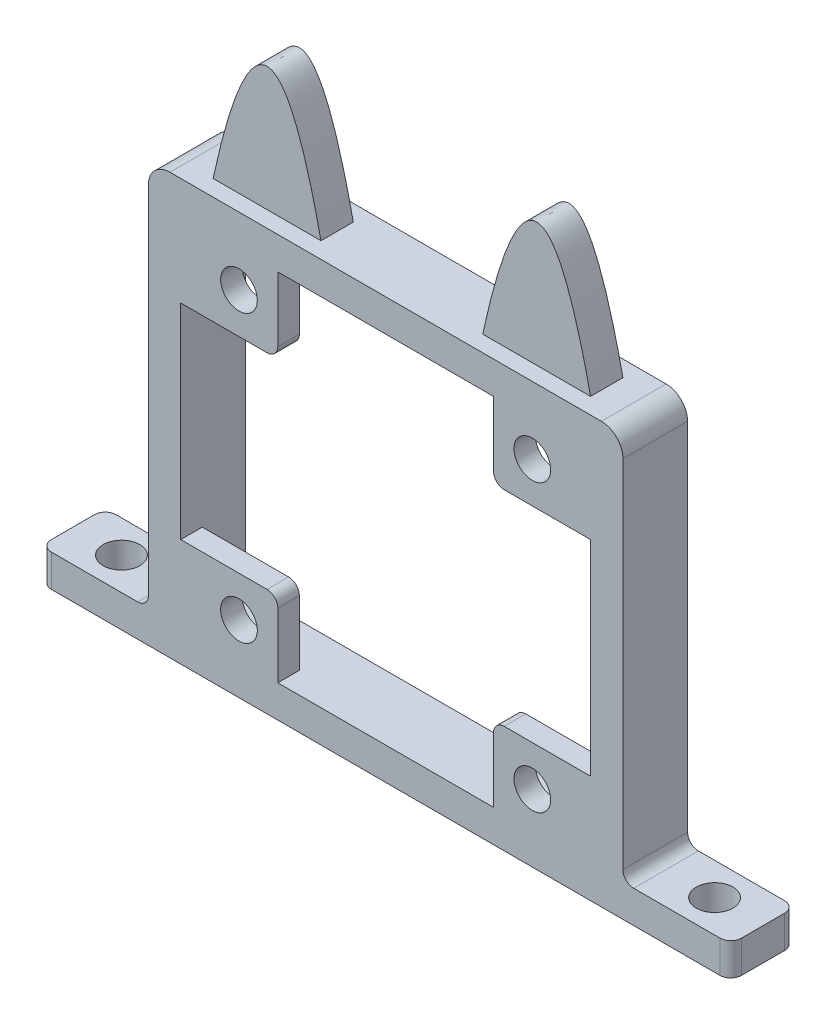
SolidWorks part; units mm, degrees
ref_plane "前视基准面" through (0, 0, 0) normal (0, 0, 1) x (1, 0, 0)
ref_plane "上视基准面" through (0, 0, 0) normal (0, 1, 0) x (1, 0, 0)
ref_plane "右视基准面" through (0, 0, 0) normal (1, 0, 0) x (0, 0, -1)
other "Configuration Table"
sketch "草图1" plane through (0, 0, 0) normal (0, 0, 1) x (1, 0, 0)
  line L1 (-19, -16.5) -> (19, -16.5)
  line L2 (-19, -16.5) -> (-19, 16.5)
  line L3 (-19, 16.5) -> (19, 16.5)
  line L4 (19, -16.5) -> (19, 16.5)
  line L5 (-19, -16.5) -> (19, 16.5) construction
  line L6 (-19, 16.5) -> (19, -16.5) construction
  line L7 (-22, -19.5) -> (22, -19.5)
  line L8 (-22, -19.5) -> (-22, 19.5)
  line L9 (-22, 19.5) -> (22, 19.5)
  line L10 (22, -19.5) -> (22, 19.5)
  line L11 (-22, -19.5) -> (22, 19.5) construction
  line L12 (-22, 19.5) -> (22, -19.5) construction
  point P0 (0, 0)
  point P5 (0, 0)
  dimension "D1" = 38
  dimension "D2" = 33
  dimension "D3" = 3
  dimension "D4" = 3
extrude "凸台-拉伸1" add sketch "草图1" along normal blind 6
sketch "草图2" plane through (0, 0, 6) normal (0, 0, 1) x (1, 0, 0)
  line L0 (10, 16.5) -> (10, 9.5)
  line L1 (19, 16.5) -> (-19, 16.5) construction
  line L2 (10, 9.5) -> (19, 9.5)
  line L3 (19, -16.5) -> (19, 16.5) construction
  line L4 (19, 9.5) -> (19, 16.5)
  line L5 (19, 16.5) -> (10, 16.5)
  line L6 (0, 16.5) -> (0, 0) construction
  line L7 (0, 0) -> (19, 0) construction
  line L8 (-19, 16.5) -> (-10, 16.5)
  line L9 (-19, 9.5) -> (-19, 16.5)
  line L10 (-10, 9.5) -> (-19, 9.5)
  line L11 (-10, 16.5) -> (-10, 9.5)
  line L12 (-10, -16.5) -> (-10, -9.5)
  line L13 (-10, -9.5) -> (-19, -9.5)
  line L14 (-19, -9.5) -> (-19, -16.5)
  line L15 (-19, -16.5) -> (-10, -16.5)
  line L16 (19, -16.5) -> (10, -16.5)
  line L17 (19, -9.5) -> (19, -16.5)
  line L18 (10, -9.5) -> (19, -9.5)
  line L19 (10, -16.5) -> (10, -9.5)
  dimension "D1" = 9
  dimension "D2" = 7
extrude "凸台-拉伸2" add sketch "草图2" against normal blind 2
sketch "草图3" plane through (0, 0, 4) normal (0, 0, -1) x (-1, 0, 0)
  line L0 (0, 16.5) -> (0, 0) construction
  line L1 (-19, 16.5) -> (19, 16.5) construction
  line L2 (0, 0) -> (19, 0) construction
  line L3 (19, 16.5) -> (19, -16.5) construction
  circle A0 centre (-13.6, 13.25) radius 1.7
  circle A1 centre (13.6, 13.25) radius 1.7
  circle A2 centre (13.6, -13.25) radius 1.7
  circle A3 centre (-13.6, -13.25) radius 1.7
  dimension "D1" = 3.4
  dimension "D2" = 27.2
  dimension "D3" = 26.5
extrude "切除-拉伸1" cut sketch "草图3" against normal through all
ref_plane "基准面1" through (0, 0, 3) normal (0, 0, -1) x (-1, 0, 0)
sketch "草图4" plane through (0, 0, 3) normal (0, 0, -1) x (-1, 0, 0)
  line L0 (-22, 19.5) -> (22, 19.5) construction
  line L1 (7.5, 19.5) -> (12.5, 42.5) construction
  line L2 (12.5, 42.5) -> (17.5, 19.5) construction
  line L3 (7.5, 19.5) -> (17.5, 19.5)
  line L4 (12.5, 42.5) -> (12.5, 19.5) construction
  line L5 (0, 19.5) -> (0, 0) construction
  line L6 (-12.5, 42.5) -> (-12.5, 19.5) construction
  line L7 (-7.5, 19.5) -> (-12.5, 42.5) construction
  line L8 (-12.5, 42.5) -> (-17.5, 19.5) construction
  line L9 (-7.5, 19.5) -> (-17.5, 19.5)
  spline S0 degree 2 poles (7.5, 19.5) (12.5, 42.5) (17.5, 19.5) knots 0 0 0 1 1 1
  spline S1 degree 2 poles (-7.5, 19.5) (-12.5, 42.5) (-17.5, 19.5) knots 0 0 0 1 1 1
  dimension "D1" = 23
  dimension "D2" = 15
  dimension "D3" = 10
extrude "凸台-拉伸3" add sketch "草图4" along normal mid plane 3
sketch "草图5" plane through (0, 0, 0) normal (0, 0, -1) x (-1, 0, 0)
  line L0 (19, -16.5) -> (-19, -16.5) construction
  line L1 (22, -19.5) -> (32, -19.5)
  line L2 (22, -19.5) -> (22, -16.5)
  line L3 (22, -16.5) -> (32, -16.5)
  line L4 (32, -19.5) -> (32, -16.5)
  line L5 (0, 16.5) -> (0, 0) construction
  line L6 (-19, 16.5) -> (19, 16.5) construction
  line L7 (-32, -19.5) -> (-32, -16.5)
  line L8 (-22, -16.5) -> (-32, -16.5)
  line L9 (-22, -19.5) -> (-22, -16.5)
  line L10 (-22, -19.5) -> (-32, -19.5)
  dimension "D1" = 10
extrude "凸台-拉伸4" add sketch "草图5" against normal up to surface (6 mm away) up to face at (15.3, -13.25, 6)
fillet "圆角3" radius 1 14 edges at (32, -18, 6) (32, -18, 0) (-32, -18, 6) (-32, -18, 0) (-22, -16.5, 3) (-19, -16.5, 2) (-10, -9.5, 5) (10, -9.5, 5) (19, -16.5, 2) (22, -16.5, 3) (-10, 9.5, 5) (-19, 16.5, 2) (10, 9.5, 5) (19, 16.5, 2)
fillet "圆角4" radius 2 2 edges at (-22, 19.5, 3) (22, 19.5, 3)
sketch "草图6" plane through (0, -16.5, 0) normal (0, 1, 0) x (1, 0, 0)
  line L0 (21.45, -3) -> (-21.45, -3) construction
  line L1 (0, 0) -> (0, -6) construction
  line L2 (20, -6) -> (-20, -6) construction
  circle A0 centre (-27.5, -3) radius 1.7
  circle A1 centre (27.5, -3) radius 1.7
  dimension "D1" = 3.4
  dimension "D2" = 55
extrude "切除-拉伸2" cut sketch "草图6" against normal blind 3
